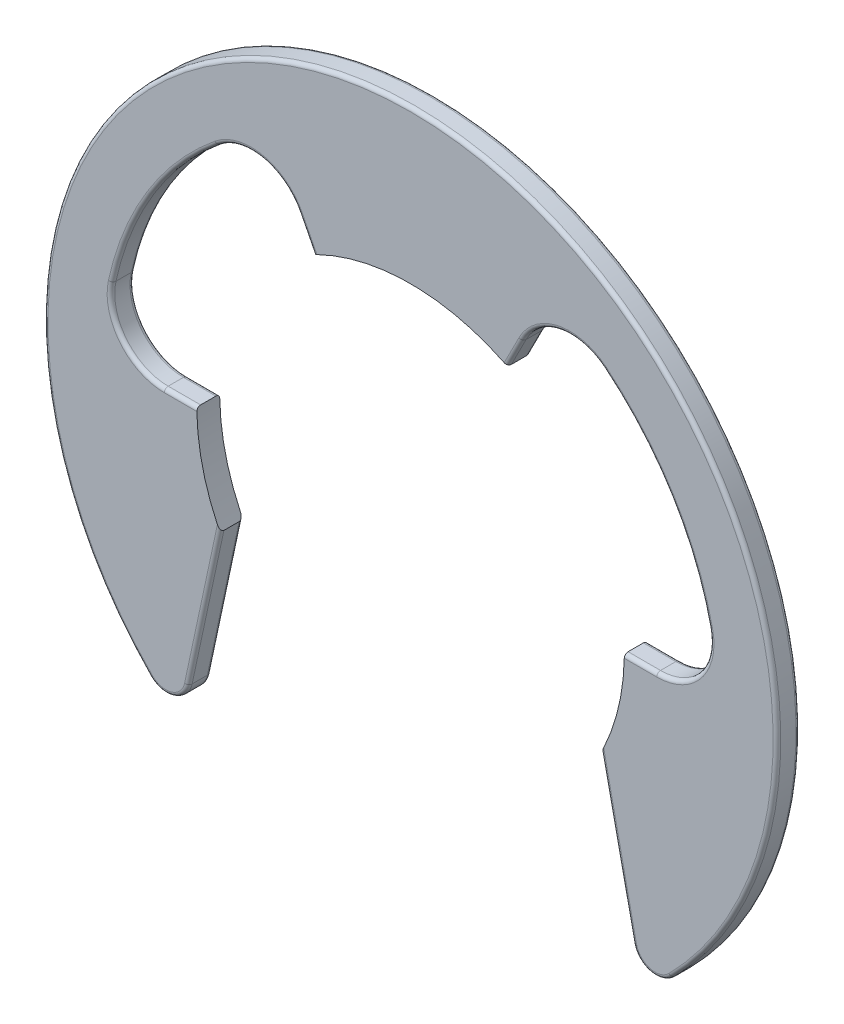
SolidWorks part; units mm, degrees
ref_plane "Front Plane" through (0, 0, 0) normal (0, 0, 1) x (1, 0, 0)
ref_plane "Top Plane" through (0, 0, 0) normal (0, 1, 0) x (1, 0, 0)
ref_plane "Right Plane" through (0, 0, 0) normal (1, 0, 0) x (0, 0, -1)
sketch "Sketch1" plane through (0, 0, 0) normal (0, 0, 1) x (1, 0, 0)
  line L0 (0, -1000) -> (0, 49000) construction
  line L1 (-1.4, 0) -> (-1.6125, 0)
  line L2 (-0.6356, 1.2474) -> (-0.732, 1.4367)
  line L3 (1.2474, -0.6356) -> (1.4557, -1.6109)
  line L4 (0.6356, 1.2474) -> (0.732, 1.4367)
  line L5 (-1.2474, -0.6356) -> (-1.4557, -1.6109)
  line L6 (1.4, 0) -> (1.6125, 0)
  arc A0 (-0.6356, 1.2474) -> (0.6356, 1.2474) centre (0, 0) cw
  arc A1 (1.2474, -0.6356) -> (1.4, 0) centre (0, 0) ccw
  arc A2 (-1.9545, 0.4242) -> (-1.2653, 1.5489) centre (0, 0) cw
  arc A3 (-1.2474, -0.6356) -> (-1.4, 0) centre (0, 0) cw
  arc A4 (1.9545, 0.4242) -> (1.2653, 1.5489) centre (0, 0) ccw
  arc A5 (-1.7092, -1.6849) -> (1.7092, -1.6849) centre (0, 0) cw
  arc A6 (1.9545, 0.4242) -> (1.6125, 0) centre (1.6125, 0.35) cw
  arc A7 (1.2653, 1.5489) -> (0.732, 1.4367) centre (1.0439, 1.2778) ccw
  arc A8 (-1.2653, 1.5489) -> (-0.732, 1.4367) centre (-1.0439, 1.2778) cw
  arc A9 (-1.6125, 0) -> (-1.9545, 0.4242) centre (-1.6125, 0.35) cw
  arc A10 (1.4557, -1.6109) -> (1.7092, -1.6849) centre (1.6023, -1.5796) ccw
  arc A11 (-1.4557, -1.6109) -> (-1.7092, -1.6849) centre (-1.6023, -1.5796) cw
  point P18 (2, 0)
  point P21 (0.908, 1.782)
  point P24 (-0.908, 1.782)
  point P27 (-2, 0)
  point P30 (1.51, -1.8654)
  point P33 (-1.51, -1.8654)
  dimension "D1" = 0.35
  dimension "D2" = 0.15
extrude "Boss-Extrude1" add sketch "Sketch1" along normal blind 0.15
fillet "Fillet1" radius 0.025 5 edges at (1.3515, -1.1232, 0.15) (1.5603, -1.7235, 0.15) (-1.3515, -1.1232, 0.15) (-1.5603, -1.7235, 0.15) (0, 2.4, 0.15)
fillet "Fillet2" radius 0.025 25 edges at (-1.5062, 0, 0) (-1.8849, 0.1303, 0) (-1.7053, 1.045, 0) (-0.9719, 1.6203, 0) (1.5062, 0, 0) (1.8849, 0.1303, 0) (1.7053, 1.045, 0) (0.9719, 1.6203, 0) (1.5062, 0, 0.15) (1.8849, 0.1303, 0.15) (1.7053, 1.045, 0.15) (0.9719, 1.6203, 0.15) (-0.6838, 1.3421, 0.15) (-0.9719, 1.6203, 0.15) (-1.7053, 1.045, 0.15) (-1.8849, 0.1303, 0.15) (1.3515, -1.1232, 0) (1.5603, -1.7235, 0) (-1.3515, -1.1232, 0) (-1.5603, -1.7235, 0) (-0.6838, 1.3421, 0) (0.6838, 1.3421, 0) (0.6838, 1.3421, 0.15) (-1.5062, 0, 0.15) (0, 2.4, 0)
